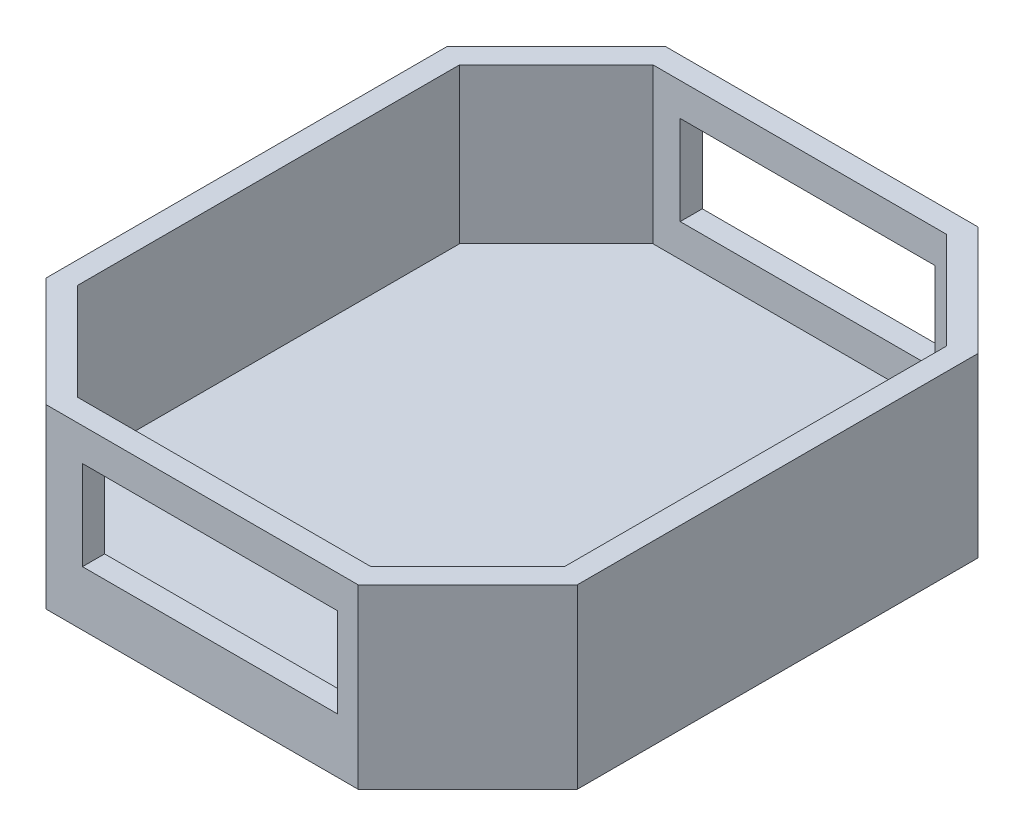
SolidWorks part; units mm, degrees
ref_plane "Front Plane" through (0, 0, 0) normal (0, 0, 1) x (1, 0, 0)
ref_plane "Top Plane" through (0, 0, 0) normal (0, 1, 0) x (1, 0, 0)
ref_plane "Right Plane" through (0, 0, 0) normal (1, 0, 0) x (0, 0, -1)
sketch "Sketch1" plane through (0, 0, 0) normal (0, 1, 0) x (1, 0, 0)
  line L0 (-152.4, 114.9382) -> (-89.5382, 177.8)
  line L1 (-152.4, -177.8) -> (152.4, -177.8)
  line L2 (-152.4, -177.8) -> (-152.4, 177.8)
  line L3 (-152.4, 177.8) -> (152.4, 177.8)
  line L4 (152.4, -177.8) -> (152.4, 177.8)
  line L5 (-152.4, -177.8) -> (152.4, 177.8) construction
  line L6 (-152.4, 177.8) -> (152.4, -177.8) construction
  line L7 (0, 177.8) -> (0, -177.8) construction
  line L8 (152.4, 114.9382) -> (89.5382, 177.8)
  line L9 (-152.4, 0) -> (152.4, 0) construction
  line L10 (152.4, -114.9382) -> (89.5382, -177.8)
  line L11 (-152.4, -114.9382) -> (-89.5382, -177.8)
  point P0 (0, 0)
  dimension "D1" = 304.8
  dimension "D2" = 355.6
  dimension "D3" = 45
  dimension "D4" = 88.9
extrude "Boss-Extrude1" add sketch "Sketch1" along normal blind 101.6 contours L2 L11 L1 L10 L4 L8 L3 L0
shell "Shell1" thickness 12.7
sketch "Sketch2" plane through (0, 0, 177.8) normal (0, 0, 1) x (1, 0, 0)
  line L1 (-68.6114, 31.527) -> (77.554, 31.527)
  line L2 (-68.6114, 31.527) -> (-68.6114, 82.7779)
  line L3 (-68.6114, 82.7779) -> (77.554, 82.7779)
  line L4 (77.554, 31.527) -> (77.554, 82.7779)
extrude "Cut-Extrude1" cut sketch "Sketch2" against normal through all both and the other way through all
